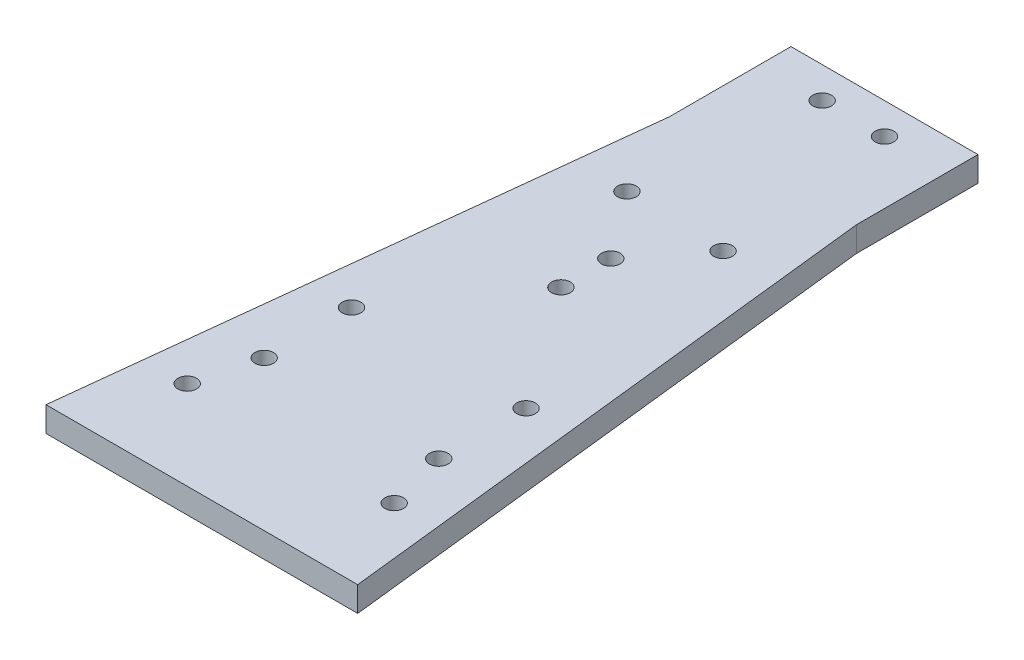
SolidWorks part; units mm, degrees
material "Thornel Mat VMA"
ref_plane "前视基准面" through (0, 0, 0) normal (0, 0, 1) x (1, 0, 0)
ref_plane "上视基准面" through (0, 0, 0) normal (0, 1, 0) x (1, 0, 0)
ref_plane "右视基准面" through (0, 0, 0) normal (1, 0, 0) x (0, 0, -1)
sketch "草图1" plane through (0, 0, 0) normal (0, 1, 0) x (1, 0, 0)
  line L0 (0, 0) -> (30, 0)
  line L1 (30, 0) -> (30, -90) construction
  line L2 (30, -90) -> (15, -90) construction
  line L3 (15, -90) -> (40, -90) construction
  line L4 (40, -90) -> (30, 0)
  line L5 (40, -90) -> (-10, -90)
  line L6 (-10, -90) -> (0, 0)
  dimension "D3" = 15
  dimension "D1" = 30
  dimension "D2" = 90
  dimension "D4" = 25
  dimension "D5" = 50
extrude "凸台-拉伸1" add sketch "草图1" along normal blind 4
sketch "草图2" plane through (0, 4, 0) normal (0, 1, 0) x (1, 0, 0)
  line L0 (15, 0) -> (15, -10) construction
  line L1 (30, 0) -> (0, 0) construction
  line L2 (15, -10) -> (24, -10) construction
  line L3 (24, -10) -> (6, -10) construction
  circle A0 centre (24, -10) radius 1.5
  circle A1 centre (6, -10) radius 1.5
  dimension "D4" = 3
  dimension "D5" = 3
  dimension "D1" = 10
  dimension "D2" = 9
  dimension "D3" = 18
sketch "草图3" plane through (0, 4, 0) normal (0, 1, 0) x (1, 0, 0)
  line L0 (15, -90) -> (15, -80) construction
  line L1 (-10, -90) -> (40, -90) construction
  line L2 (15, -80) -> (32, -80) construction
  line L3 (32, -80) -> (-2, -80) construction
  circle A0 centre (32, -80) radius 1.5
  circle A1 centre (-2, -80) radius 1.5
  dimension "D4" = 3
  dimension "D5" = 3
  dimension "D1" = 10
  dimension "D2" = 17
  dimension "D3" = 34
sketch "草图4" plane through (0, 4, 0) normal (0, 1, 0) x (1, 0, 0)
  line L0 (-10, -90) -> (40, -90) construction
  line L1 (15, -80) -> (15, -66) construction
  line L2 (15, -66) -> (1, -66) construction
  line L3 (1, -66) -> (29, -66) construction
  line L4 (15, -66) -> (15, -52) construction
  line L5 (15, -52) -> (1, -52) construction
  line L6 (1, -52) -> (29, -52) construction
  circle A0 centre (1, -66) radius 1.5
  circle A1 centre (1, -52) radius 1.5
  circle A2 centre (29, -66) radius 1.5
  circle A3 centre (29, -52) radius 1.5
  dimension "D6" = 3
  dimension "D7" = 3
  dimension "D8" = 3
  dimension "D9" = 3
  dimension "D1" = 24
  dimension "D2" = 14
  dimension "D3" = 28
  dimension "D4" = 14
  dimension "D5" = 28
extrude "切除-拉伸3" cut sketch "草图4" against normal through all
sketch "草图5" plane through (0, 4, 0) normal (0, 1, 0) x (1, 0, 0)
  line L0 (1, -52) -> (29, -52) construction
  line L1 (15, -52) -> (15, -32.4) construction
  line L2 (15, -32.4) -> (15, -24.4) construction
  circle A0 centre (15, -32.4) radius 1.5
  circle A1 centre (15, -24.4) radius 1.5
  dimension "D3" = 3
  dimension "D4" = 3
  dimension "D1" = 19.6
  dimension "D2" = 8
extrude "切除-拉伸4" cut sketch "草图5" against normal through all
sketch "草图9" plane through (0, 4, 0) normal (0, 1, 0) x (1, 0, 0)
  line L8 (40, -90) -> (30, 0)
  line L9 (30, 0) -> (0, 0)
  line L10 (0, 0) -> (-10, -90)
  line L11 (-10, -90) -> (40, -90)
  circle A0 centre (6.9632, -13.7788) radius 1.5
  circle A1 centre (22.9531, -14.3472) radius 1.5
  circle A2 centre (-1.6, -75.75) radius 1.5
  circle A3 centre (31.6, -75.75) radius 1.5
  dimension "D2" = 3
  dimension "D3" = 3
  dimension "D4" = 3
  dimension "D5" = 3
extrude "切除-拉伸6" cut sketch "草图9" against normal blind 10 contours A0 | A1 | A2 | A3
sketch "草图10" plane through (0, 0, 0) normal (0, 0, -1) x (-1, 0, 0)
  line L1 (0, 0) -> (-30, 0)
  line L2 (0, 0) -> (0, 4)
  line L3 (0, 4) -> (-30, 4)
  line L4 (-30, 0) -> (-30, 4)
extrude "凸台-拉伸2" add sketch "草图10" along normal blind 19.5
sketch "草图11" plane through (0, 0, 0) normal (0, -1, 0) x (1, 0, 0)
  line L0 (15, -19.5) -> (15, -14.5) construction
  line L1 (30, -19.5) -> (0, -19.5) construction
  line L2 (15, -14.5) -> (10, -14.5) construction
  line L3 (10, -14.5) -> (20, -14.5) construction
  circle A0 centre (10, -14.5) radius 1.5
  circle A1 centre (20, -14.5) radius 1.5
  dimension "D4" = 3
  dimension "D5" = 3
  dimension "D1" = 5
  dimension "D2" = 5
  dimension "D3" = 10
extrude "切除-拉伸7" cut sketch "草图11" against normal through all
